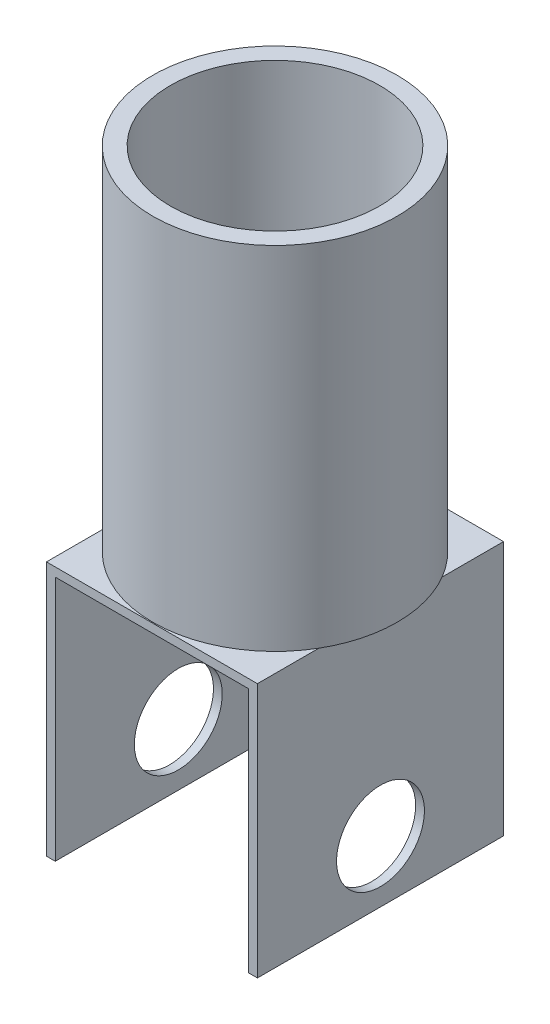
SolidWorks part; units mm, degrees
material "6061-T6 (SS)"
ref_plane "Front Plane" through (0, 0, 0) normal (0, 0, 1) x (1, 0, 0)
ref_plane "Top Plane" through (0, 0, 0) normal (0, 1, 0) x (1, 0, 0)
ref_plane "Right Plane" through (0, 0, 0) normal (1, 0, 0) x (0, 0, -1)
sketch "Sketch1" plane through (0, 0, 0) normal (0, 1, 0) x (1, 0, 0)
  circle A0 centre (0, 0) radius 69.5
  circle A1 centre (0, 0) radius 59.5
  dimension "D1" = 139
  dimension "D2" = 10
extrude "Boss-Extrude1" add sketch "Sketch1" along normal blind 200
sketch "Sketch2" plane through (0, 0, 0) normal (0, -1, 0) x (1, 0, 0)
  line L1 (-60, -70) -> (60, -70)
  line L2 (-60, -70) -> (-60, 70)
  line L3 (-60, 70) -> (60, 70)
  line L4 (60, -70) -> (60, 70)
  line L5 (-60, -70) -> (60, 70) construction
  line L6 (-60, 70) -> (60, -70) construction
  point P0 (0, 0)
  dimension "D1" = 120
  dimension "D2" = 140
extrude "Boss-Extrude2" add sketch "Sketch2" along normal blind 5
sketch "Sketch3" plane through (0, -5, 0) normal (0, -1, 0) x (1, 0, 0)
  line L0 (-60, -70) -> (60, -70) construction
  line L1 (-60, 70) -> (-55, 70)
  line L2 (-60, 70) -> (-60, -70)
  line L3 (-60, -70) -> (-55, -70)
  line L4 (-55, 70) -> (-55, -70)
  line L6 (60, 70) -> (55, 70)
  line L7 (60, 70) -> (60, -70)
  line L8 (60, -70) -> (55, -70)
  line L9 (55, 70) -> (55, -70)
  dimension "D1" = 5
  dimension "D2" = 5
extrude "Boss-Extrude3" add sketch "Sketch3" along normal blind 140
sketch "Sketch4" plane through (-60, 0, 0) normal (-1, 0, 0) x (0, 0, 1)
  line L0 (0, 0) -> (0, -135) construction
  line L1 (-35.0749, 0) -> (35.0749, 0) construction
  line L2 (70, -145) -> (-70, -145) construction
  circle A0 centre (0, -110) radius 25
  dimension "D1" = 50
  dimension "D2" = 35
extrude "Cut-Extrude1" cut sketch "Sketch4" against normal through all both and the other way through all
